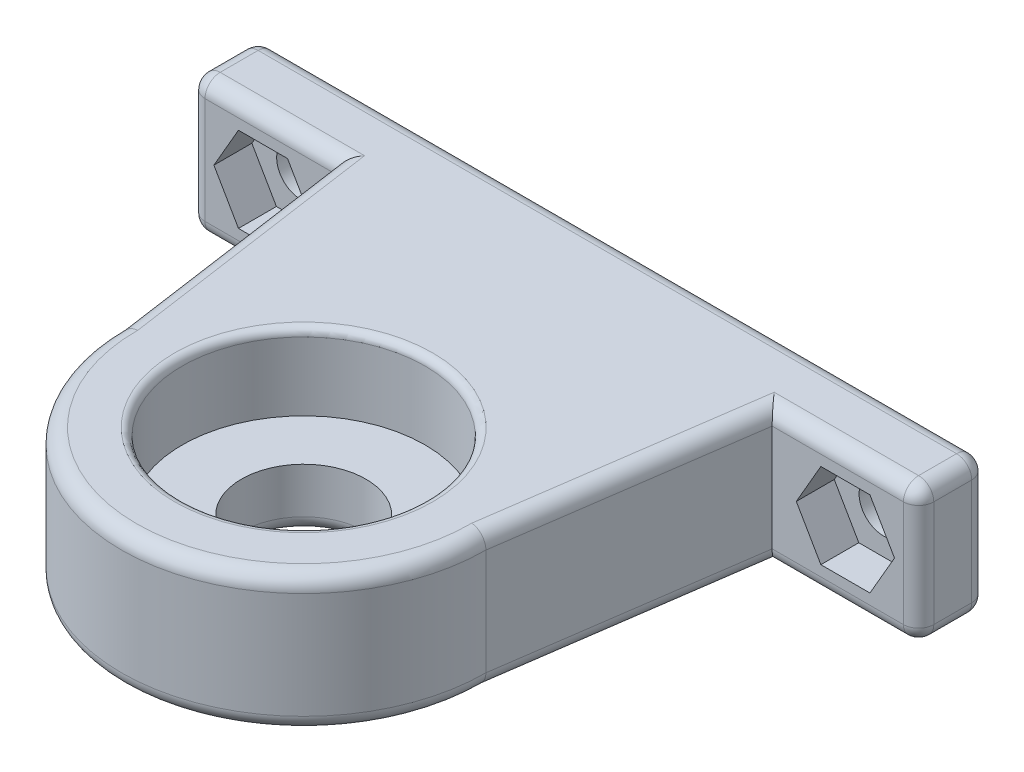
SolidWorks part; units mm, degrees
ref_plane "Alzado" through (0, 0, 0) normal (0, 0, 1) x (1, 0, 0)
ref_plane "Planta" through (0, 0, 0) normal (0, 1, 0) x (1, 0, 0)
ref_plane "Vista lateral" through (0, 0, 0) normal (1, 0, 0) x (0, 0, -1)
sketch "Croquis1" plane through (0, 0, 0) normal (0, 1, 0) x (1, 0, 0)
  line L0 (-12.5027, 9.6432) -> (-10.1455, -6.8568)
  line L1 (-13.1455, 14.1432) -> (16.8545, 14.1432)
  line L2 (1.8545, -6.8568) -> (1.8545, 30.0374) construction
  line L3 (-13.1455, 14.1432) -> (-20.1455, 14.1432)
  line L4 (16.8545, 9.6432) -> (16.2116, 9.6432)
  line L5 (-13.1455, 9.6432) -> (-20.1455, 9.6432)
  line L6 (16.2116, 9.6432) -> (13.8545, -6.8568)
  line L8 (-13.1455, 9.6432) -> (-12.5027, 9.6432)
  line L9 (16.8545, 14.1432) -> (23.8545, 14.1432)
  line L11 (16.8545, 9.6432) -> (23.8545, 9.6432)
  line L12 (23.8545, 14.1432) -> (25.8545, 14.1432)
  line L13 (-20.1455, 14.1432) -> (-22.1455, 14.1432)
  line L15 (-20.1455, 9.6432) -> (-22.1455, 9.6432)
  line L16 (-22.1455, 14.1432) -> (-22.1455, 9.6432)
  line L17 (23.8545, 9.6432) -> (25.8545, 9.6432)
  line L18 (25.8545, 14.1432) -> (25.8545, 9.6432)
  circle A0 centre (1.8545, -6.8568) radius 8
  circle A1 centre (1.8545, -6.8568) radius 12
  circle A2 centre (1.8545, -6.8568) radius 4.1
  dimension "D3" = 16
  dimension "D7" = 2
  dimension "D1" = 30
  dimension "D2" = 21
  dimension "D5" = 7
  dimension "D6" = 4.5
  dimension "D8" = 2
  dimension "D4" = 4
extrude "Saliente-Extruir2" add sketch "Croquis1" along normal blind 9
sketch "Croquis2" plane through (0, 9, 0) normal (0, 1, 0) x (1, 0, 0)
  circle A0 centre (1.8545, -6.8568) radius 4.1 construction
  circle A1 centre (1.8545, -6.8568) radius 4.1
  circle A2 centre (1.8545, -6.8568) radius 8
extrude "Cortar-Extruir1" cut sketch "Croquis2" against normal blind 5
sketch "Croquis3" plane through (0, 0, -9.6432) normal (0, 0, 1) x (1, 0, 0)
  line L0 (-12.5027, 9) -> (-22.1455, 0) construction
  line L2 (-14.0909, 4.5) -> (-15.7075, 7.3)
  line L3 (-15.7075, 7.3) -> (-18.9407, 7.3)
  line L12 (-18.9407, 7.3) -> (-20.5573, 4.5)
  line L13 (-20.5573, 4.5) -> (-18.9407, 1.7)
  line L14 (-18.9407, 1.7) -> (-15.7075, 1.7)
  line L15 (-15.7075, 1.7) -> (-14.0909, 4.5)
  circle A0 centre (-17.3241, 4.5) radius 2.8 construction
  dimension "D2" = 5.6
extrude "Cortar-Extruir3" cut sketch "Croquis3" against normal blind 2.5
sketch "Croquis4" plane through (0, 0, -9.6432) normal (0, 0, 1) x (1, 0, 0)
  line L0 (25.8545, 9) -> (16.2116, 0) construction
  line L1 (16.2116, 9) -> (16.2116, 0) construction
  line L2 (25.8545, 0) -> (16.2116, 0) construction
  line L4 (24.2662, 4.5) -> (22.6496, 7.3)
  line L5 (22.6496, 7.3) -> (19.4165, 7.3)
  line L6 (19.4165, 7.3) -> (17.7999, 4.5)
  line L7 (17.7999, 4.5) -> (19.4165, 1.7)
  line L8 (19.4165, 1.7) -> (22.6496, 1.7)
  line L9 (22.6496, 1.7) -> (24.2662, 4.5)
  circle A0 centre (21.033, 4.5) radius 2.8 construction
  dimension "D1" = 5.6
extrude "Cortar-Extruir4" cut sketch "Croquis4" against normal blind 2.5
sketch "Croquis5" plane through (0, 0, -12.1432) normal (0, 0, 1) x (1, 0, 0)
  line L0 (17.7999, 4.5) -> (24.2662, 4.5) construction
  line L1 (-20.5573, 4.5) -> (-14.0909, 4.5) construction
  circle A0 centre (21.033, 4.5) radius 1.6
  circle A1 centre (-17.3241, 4.5) radius 1.6
extrude "Cortar-Extruir5" cut sketch "Croquis5" against normal blind 2.5
fillet "Redondeo1" radius 1 21 edges at (1.8545, 0, 10.9568) (-17.3241, 0, -9.6432) (-11.3241, 0, -1.3932) (1.8545, 0, 18.8568) (15.033, 0, -1.3932) (21.033, 0, -9.6432) (1.8545, 0, -14.1432) (21.033, 9, -9.6432) (15.033, 9, -1.3932) (1.8545, 9, 18.8568) (-11.3241, 9, -1.3932) (-17.3241, 9, -9.6432) (1.8545, 9, -14.1432) (25.8545, 9, -11.8932) (-22.1455, 9, -11.8932) (-22.1455, 0, -11.8932) (25.8545, 0, -11.8932) (-22.1455, 4.5, -9.6432) (-22.1455, 4.5, -14.1432) (25.8545, 4.5, -9.6432) (25.8545, 4.5, -14.1432)
fillet "Redondeo2" radius 0.5 1 edges at (1.8545, 9, 14.8568)
